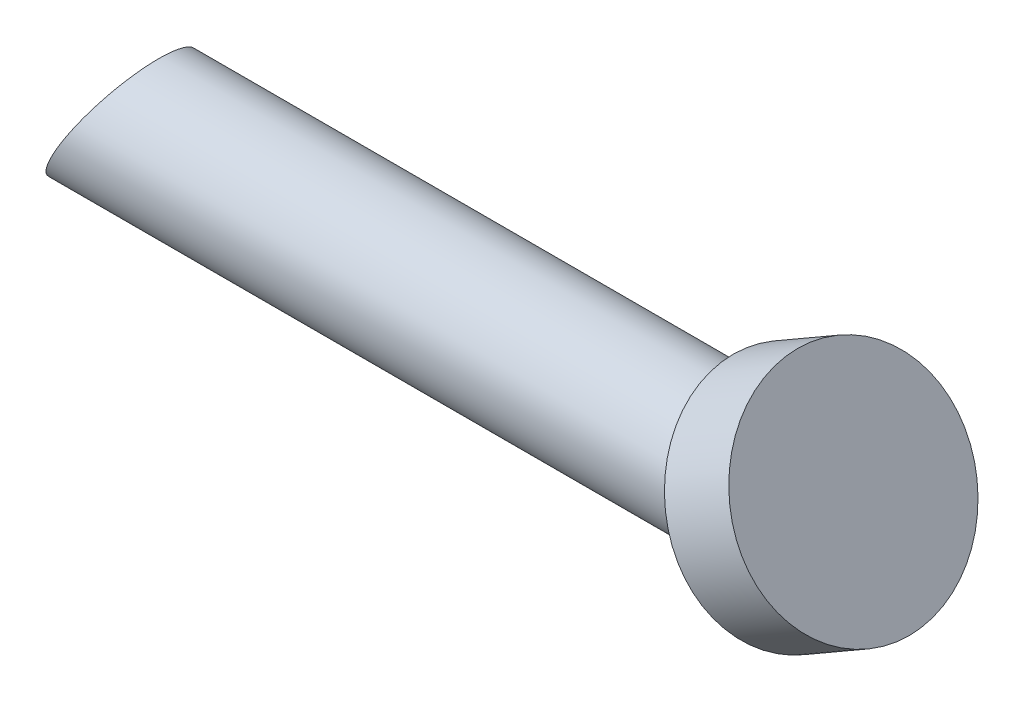
SolidWorks part; units mm, degrees
ref_plane "Front Plane" through (0, 0, 0) normal (0, 0, 1) x (1, 0, 0)
ref_plane "Top Plane" through (0, 0, 0) normal (0, 1, 0) x (1, 0, 0)
ref_plane "Right Plane" through (0, 0, 0) normal (1, 0, 0) x (0, 0, -1)
sketch "Sketch1" plane through (0, 0, 0) normal (1, 0, 0) x (0, 0, -1)
  circle A0 centre (0, 0) radius 0.875
  dimension "D1" = 1.75
extrude "Boss-Extrude1" add sketch "Sketch1" along normal mid plane 10
sketch "Sketch2" plane through (0, 0, 0) normal (0, 0, 1) x (1, 0, 0)
  line L0 (-5, -0.875) -> (-3.9896, 0.875)
  line L1 (5, 0.875) -> (-5, 0.875) construction
  line L2 (5, -0.875) -> (3.9896, 0.875)
  line L4 (5, -0.875) -> (5, 0.875) construction
  line L5 (-5, 0.875) -> (-5, -0.875) construction
  line L6 (5, -0.875) -> (5, 0.875)
  line L7 (5, 0.875) -> (-5, 0.875)
  line L8 (-5, 0.875) -> (-5, -0.875)
  point P11 (4.0098, 0.875)
  point P12 (-3.2342, 0.875)
  dimension "D1" = 30
  dimension "D2" = 30
extrude "Cut-Extrude1" cut sketch "Sketch2" against normal through all and the other way through all contours L7 L8 L0 | L6 L7 L2
sketch "Sketch3" plane through (3.3711, 1.9463, 0) normal (0.866, 0.5, 0) x (0, 0, -1)
  circle A0 centre (0, -2.2474) radius 1.5
  ellipse E0 centre (0, -2.2474) end of major axis (0, -1.237) minor radius 0.875 construction
  dimension "D1" = 3
extrude "Boss-Extrude2" add sketch "Sketch3" along normal blind 1
